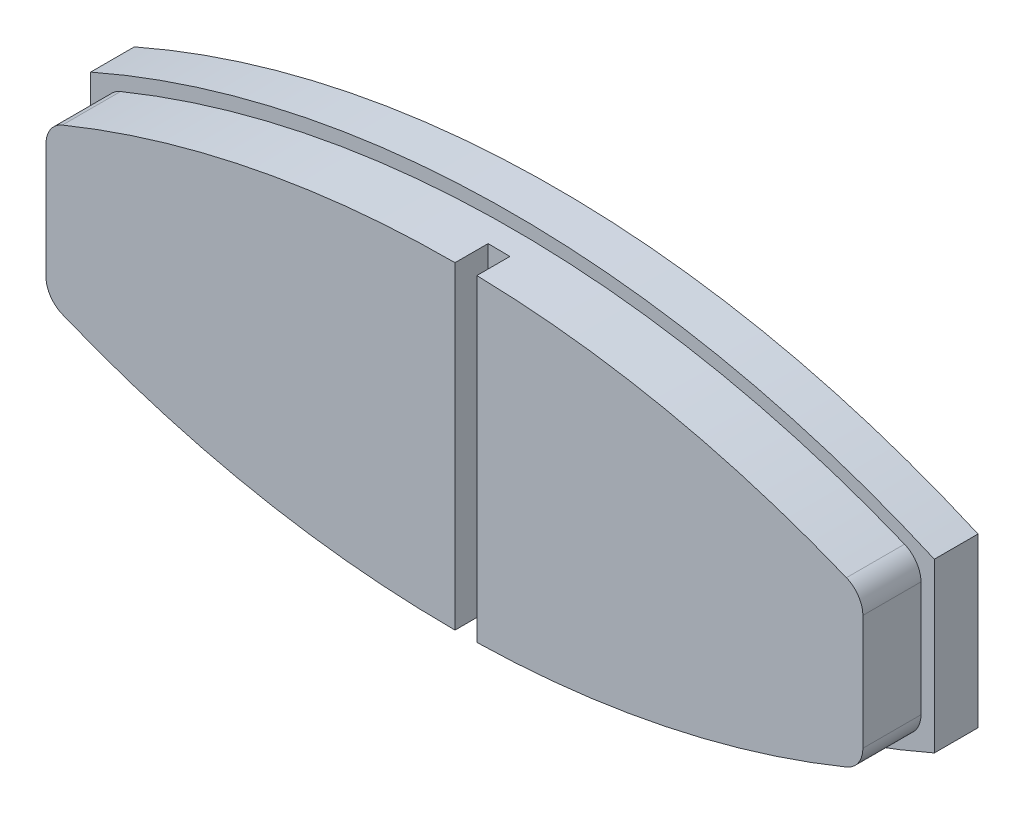
SolidWorks part; units mm, degrees
ref_plane "Front Plane" through (0, 0, 0) normal (0, 0, 1) x (1, 0, 0)
ref_plane "Top Plane" through (0, 0, 0) normal (0, 1, 0) x (1, 0, 0)
ref_plane "Right Plane" through (0, 0, 0) normal (1, 0, 0) x (0, 0, -1)
sketch "Sketch1" plane through (0, 0, 0) normal (0, 0, 1) x (1, 0, 0)
  line L0 (-31.9214, 6.35) -> (-31.9214, -6.35)
  line L1 (0, 0) -> (-17.9324, 0) construction
  line L2 (0, 0) -> (0, 13.0556) construction
  line L3 (31.9214, 6.35) -> (31.9214, -6.35)
  arc A0 (31.9214, 6.35) -> (-31.9214, 6.35) centre (0, -66.2769) ccw
  arc A1 (31.9214, -6.35) -> (-31.9214, -6.35) centre (0, 66.2769) cw
  point P8 (-31.9214, 0)
  dimension "D3" = 31.9214
  dimension "D1" = 13.0556
  dimension "D2" = 12.7
extrude "Boss-Extrude1" add sketch "Sketch1" along normal blind 3.302
sketch "Sketch2" plane through (0, 0, 3.302) normal (0, 0, 1) x (1, 0, 0)
  line L4 (-30.9054, 5.6837) -> (-30.9055, -5.6837)
  line L5 (30.9054, -5.6837) -> (30.9054, 5.6837)
  line L6 (-30.9054, 5.6837) -> (-30.9055, -5.6837)
  line L7 (30.9054, -5.6837) -> (30.9054, 5.6837)
  arc A4 (30.9054, 5.6837) -> (-30.9054, 5.6837) centre (0, -66.2769) ccw
  arc A5 (-30.9055, -5.6837) -> (30.9054, -5.6837) centre (0, 66.2769) ccw
  arc A6 (30.9054, 5.6837) -> (-30.9054, 5.6837) centre (0, -66.2769) ccw
  arc A7 (-30.9055, -5.6837) -> (30.9054, -5.6837) centre (0, 66.2769) ccw
  dimension "D1" = 1.016
extrude "Boss-Extrude2" add sketch "Sketch2" along normal blind 4.3942 separate body
sketch "Sketch3" plane through (0, 0, 0) normal (0, 0, -1) x (-1, 0, 0)
  line L0 (0, 0) -> (0, 8.5723) construction
  circle A0 centre (-23.8125, 0) radius 3.35
  circle A1 centre (23.8125, 0) radius 3.35
  dimension "D1" = 6.7
  dimension "D2" = 23.8125
extrude "Cut-Extrude1" cut sketch "Sketch3" against normal blind 6.35
sketch "Sketch6" plane through (0, 0, 7.6962) normal (0, 0, 1) x (1, 0, 0)
  line L0 (30.9054, -5.6837) -> (30.9054, 5.6837) construction
  line L1 (0.0445, 18.5168) -> (1.6955, 18.5168)
  line L2 (0.0445, 18.5168) -> (0.0445, -19.1088)
  line L3 (0.0445, -19.1088) -> (1.6955, -19.1088)
  line L4 (1.6955, 18.5168) -> (1.6955, -19.1088)
  dimension "D1" = 1.651
  dimension "D2" = 29.21
extrude "Cut-Extrude2" cut sketch "Sketch6" against normal blind 2.5
fillet "Fillet1" radius 2 4 edges at (-30.9055, -5.6837, 5.4991) (-30.9054, 5.6837, 5.4991) (30.9054, 5.6837, 5.4991) (30.9054, -5.6837, 5.4991)
sketch "Sketch7" plane through (0, 0, 3.302) normal (0, 0, 1) x (1, 0, 0)
  line L0 (0.87, 12.0348) -> (0.87, 13.6223) construction
  line L1 (0.87, 13.6223) -> (0.87, -113.3777) construction
  arc A0 (1.6955, 12.0212) -> (0.0445, 12.0396) centre (0, -66.2769) ccw construction
  circle A1 centre (0.87, -113.3777) radius 127
  dimension "D1" = 1.5875
  dimension "D2" = 127
sketch "Sketch8" plane through (0, 0, 3.302) normal (0, 0, 1) x (1, 0, 0)
  line L0 (0.87, 12.0348) -> (0.87, 13.0508) construction
  line L1 (0.87, 13.0508) -> (0.87, -148.2392) construction
  arc A0 (1.6955, 12.0212) -> (0.0445, 12.0396) centre (0, -66.2769) ccw construction
  circle A1 centre (0.87, -148.2392) radius 161.29
  dimension "D1" = 1.016
  dimension "D2" = 161.29
